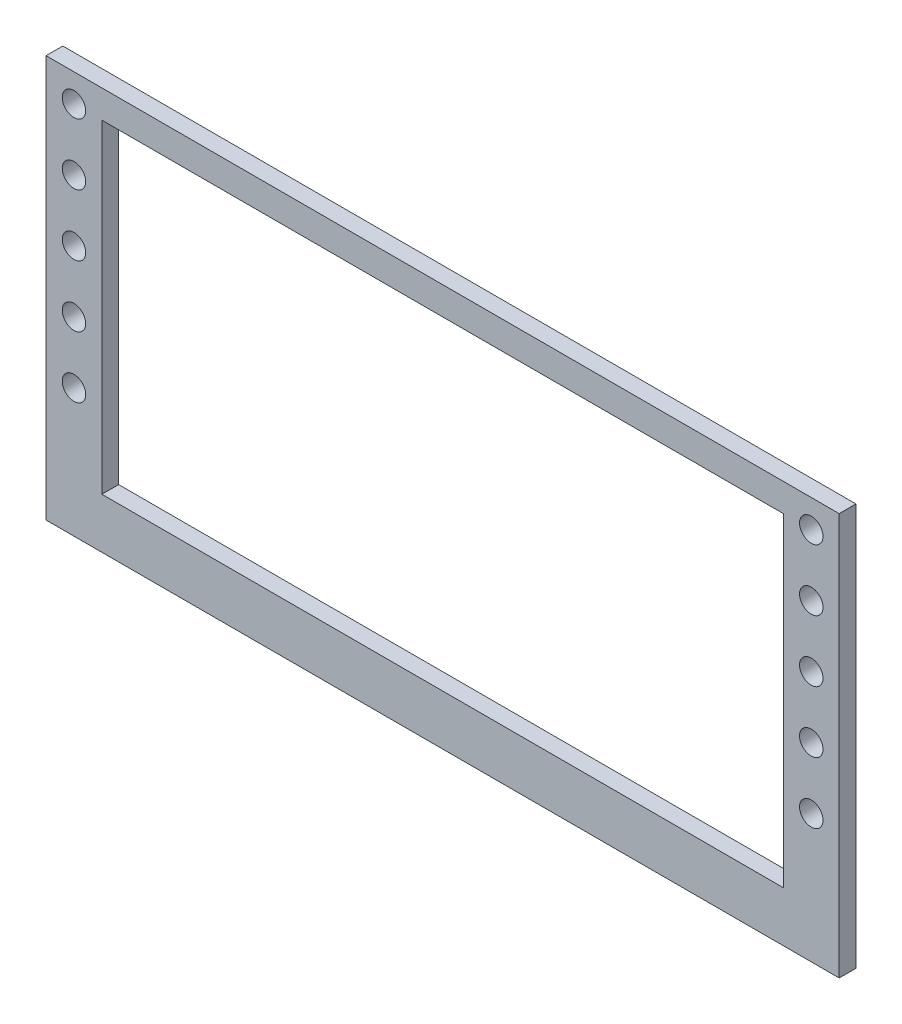
SolidWorks part; units mm, degrees
ref_plane "Front Plane" through (0, 0, 0) normal (0, 0, 1) x (1, 0, 0)
ref_plane "Top Plane" through (0, 0, 0) normal (0, 1, 0) x (1, 0, 0)
ref_plane "Right Plane" through (0, 0, 0) normal (1, 0, 0) x (0, 0, -1)
sketch "Sketch2" plane through (0, 0, 0) normal (0, 0, 1) x (1, 0, 0)
  line L1 (0, 72) -> (142, 72)
  line L2 (0, 72) -> (0, 0)
  line L3 (0, 0) -> (142, 0)
  line L4 (142, 72) -> (142, 0)
  line L5 (10, 67) -> (132, 67)
  line L6 (10, 67) -> (10, 9)
  line L7 (10, 9) -> (132, 9)
  line L8 (132, 67) -> (132, 9)
  circle A0 centre (5, 67) radius 2.1
  circle A1 centre (5, 56) radius 2.1
  circle A2 centre (5, 45) radius 2.1
  circle A3 centre (5, 34) radius 2.1
  circle A4 centre (5, 23) radius 2.1
  circle A5 centre (137, 67) radius 2.1
  circle A6 centre (137, 56) radius 2.1
  circle A7 centre (137, 45) radius 2.1
  circle A8 centre (137, 34) radius 2.1
  circle A9 centre (137, 23) radius 2.1
  point P28 (0, 0)
  point P29 (0, 0)
  point P30 (0, 0)
  point P31 (0, 0)
  point P32 (0, 0)
  point P33 (0, 0)
  point P34 (0, 0)
  point P35 (0, 0)
  point P36 (0, 0)
  point P37 (0, 0)
  point P38 (0, 0)
  point P39 (0, 0)
  point P41 (0, 0)
  point P42 (0, 0)
  point P43 (0, 0)
  point P44 (0, 0)
  dimension "D5" = 4.2
  dimension "D1" = 142
  dimension "D2" = 72
  dimension "D4" = 122
  dimension "D6" = 11
  dimension "D7" = 11
  dimension "D8" = 11
  dimension "D9" = 11
  dimension "D10" = 132
  dimension "D11" = 5
  dimension "D12" = 10
  dimension "D13" = 58
  dimension "D14" = 5
  dimension "D15" = 44
extrude "Boss-Extrude1" add sketch "Sketch2" along normal blind 3
